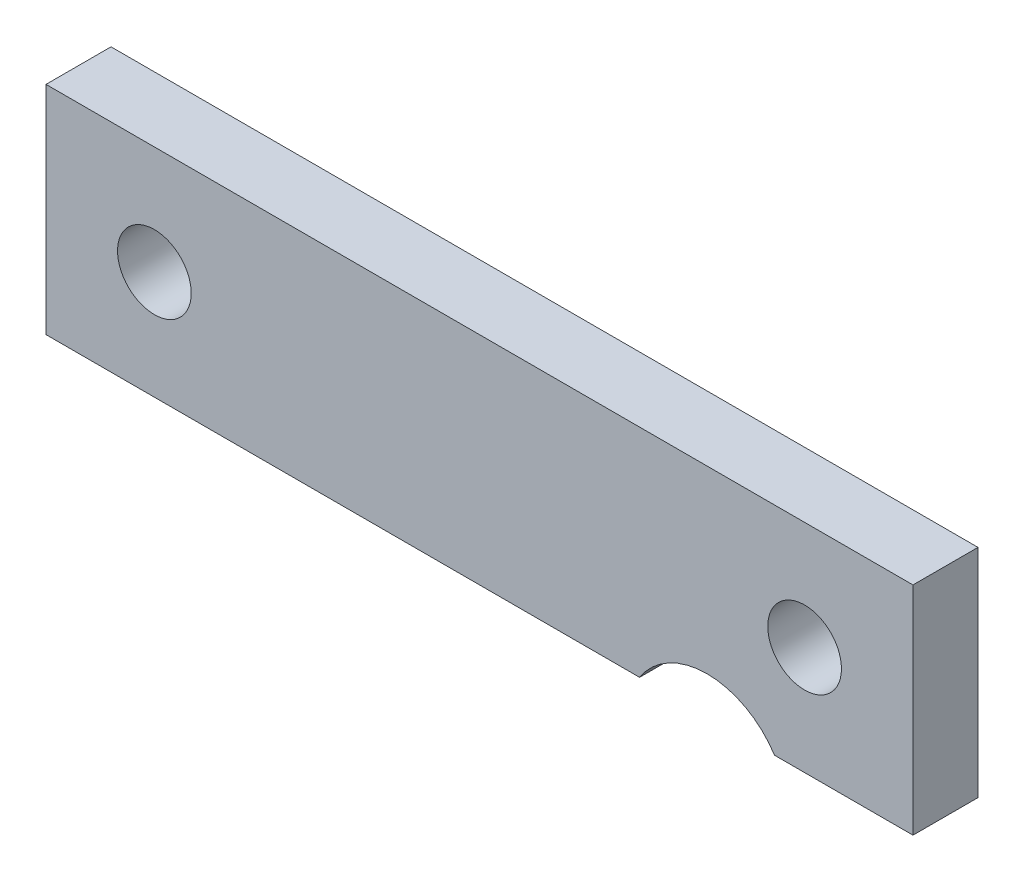
SolidWorks part; units mm, degrees
other "Platform Joint Strap 2 Right"
ref_plane "Front Plane" through (0, 0, 0) normal (0, 0, 1) x (1, 0, 0)
ref_plane "Top Plane" through (0, 0, 0) normal (0, 1, 0) x (1, 0, 0)
ref_plane "Right Plane" through (0, 0, 0) normal (1, 0, 0) x (0, 0, -1)
sketch3d "Main Profile Sketch datum points"
  point P0 (0, 0, 44.5)
  point P1 (10, 0, 44.5)
  point P2 (0, 10, 44.5)
ref_plane "Main Profile Sketch plane" through (0, 0, 44.5) normal (0, 0, 1) x (1, 0, 0)
sketch "Main Profile Sketch" plane through (0, 0, 44.5) normal (0, 0, 1) x (1, 0, 0)
  line L0 (35, -31.5) -> (75, -31.5)
  line L1 (75, -31.5) -> (75, -41.5)
  line L2 (68.6129, -41.5) -> (75, -41.5)
  line L3 (35, -41.5) -> (62.3871, -41.5)
  line L4 (35, -31.5) -> (35, -41.5)
  arc A0 (68.6129, -41.5) -> (62.3871, -41.5) centre (65.5, -43.5) ccw
  circle A1 centre (40, -36.5) radius 1.7
  circle A2 centre (70, -36.5) radius 1.7
extrude "Main Extrusion" add sketch "Main Profile Sketch" against normal blind 3 separate body
